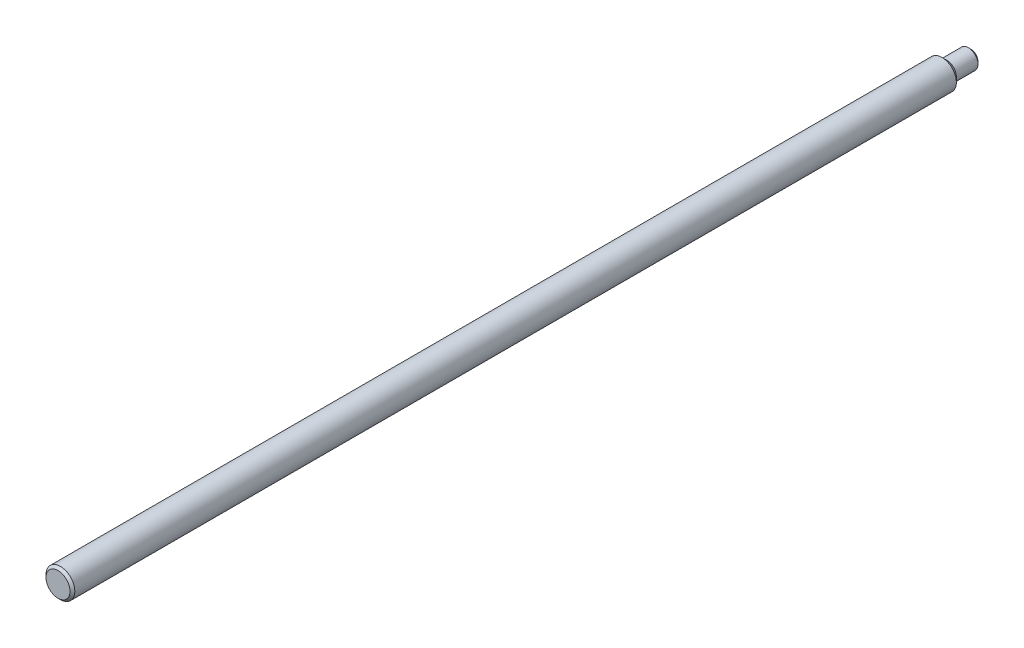
SolidWorks part; units mm, degrees
ref_plane "Piano frontale" through (0, 0, 0) normal (0, 0, 1) x (1, 0, 0)
ref_plane "Piano superiore" through (0, 0, 0) normal (0, 1, 0) x (1, 0, 0)
ref_plane "Piano destro" through (0, 0, 0) normal (1, 0, 0) x (0, 0, -1)
sketch "Schizzo1" plane through (0, 0, 0) normal (0, 0, 1) x (1, 0, 0)
  circle A0 centre (0, 0) radius 6
  dimension "D1" = 12
extrude "Estrusione-Estrusione1" add sketch "Schizzo1" along normal blind 380
cosmetic thread "Filettatura cosmetica1" parameters "D2"=10.344
sketch "Schizzo2" plane through (0, 0, 0) normal (0, 1, 0) x (1, 0, 0)
  line L0 (0, 1.8987) -> (0, -61.2971) construction
  line L1 (-4, -10) -> (-6, -12)
  line L2 (-6, -12) -> (-6, 0)
  line L3 (-6, 0) -> (-4, 0)
  line L4 (-4, 0) -> (-4, -10)
  line L5 (-6, 0) -> (-6, -380) construction
  line L6 (6, 0) -> (-6, 0) construction
  dimension "D1" = 8
  dimension "D2" = 135
  dimension "D3" = 10
revolve "Taglia-Rivoluzione1" cut sketch "Schizzo2" angle 360 about L0
chamfer "Smusso1" distance 1 angle 45 2 edges at (-4, 0, 0) (6, 0, 380)
sketch "Schizzo3" plane through (0, 0, 0) normal (0, 1, 0) x (1, 0, 0)
  line L0 (-4, -10) -> (-4, -10.2926)
